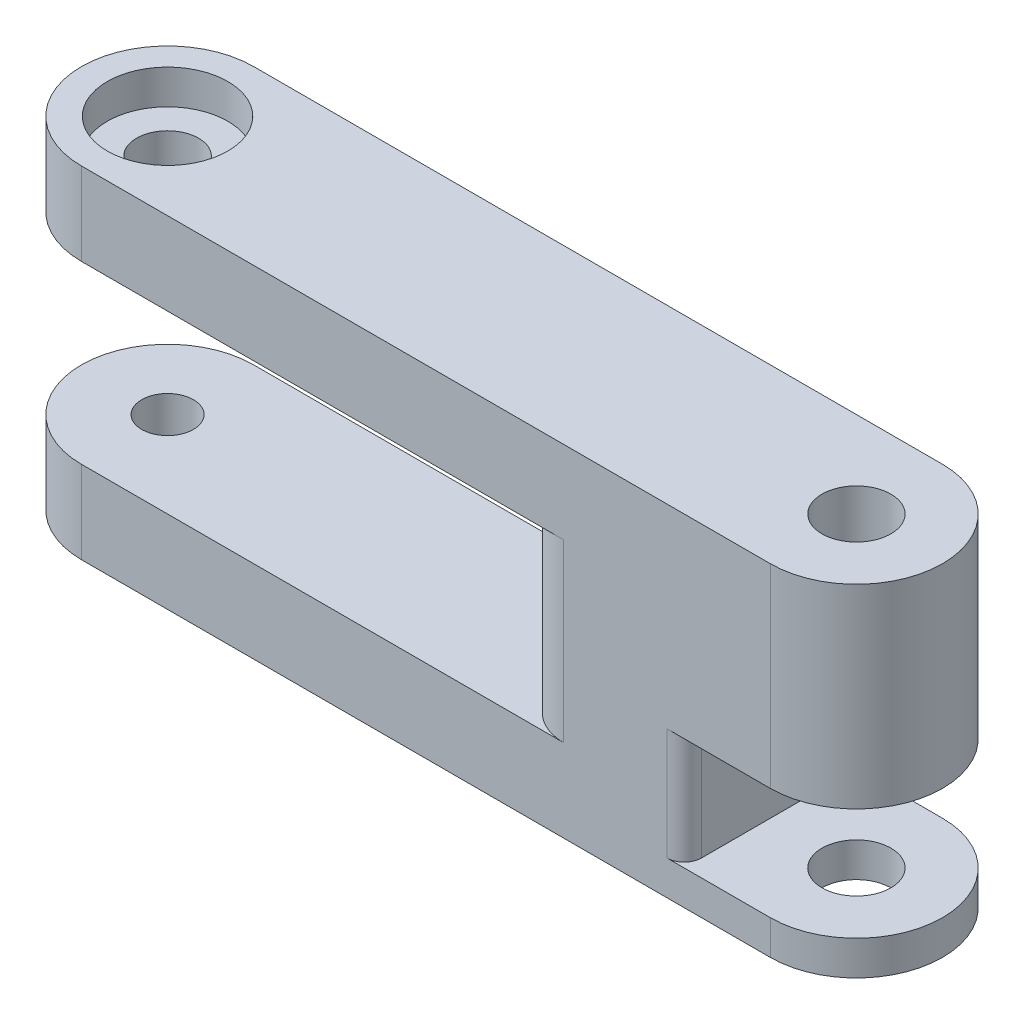
SolidWorks part; units mm, degrees
ref_plane "Front Plane" through (0, 0, 0) normal (0, 0, 1) x (1, 0, 0)
ref_plane "Top Plane" through (0, 0, 0) normal (0, 1, 0) x (1, 0, 0)
ref_plane "Right Plane" through (0, 0, 0) normal (1, 0, 0) x (0, 0, -1)
sketch "Sketch1" plane through (0, 0, 0) normal (0, 1, 0) x (1, 0, 0)
  line L0 (-25.4, 0) -> (25.4, 0) construction
  line L1 (-25.4, 6.35) -> (25.4, 6.35)
  line L2 (-25.4, -6.35) -> (25.4, -6.35)
  arc A0 (-25.4, 6.35) -> (-25.4, -6.35) centre (-25.4, 0) ccw
  arc A1 (25.4, -6.35) -> (25.4, 6.35) centre (25.4, 0) ccw
  circle A2 centre (-25.4, 0) radius 2.286
  circle A3 centre (25.4, 0) radius 2.54
  point P2 (0, 0)
  dimension "D3" = 4.572
  dimension "D4" = 5.08
  dimension "D1" = 50.8
  dimension "D2" = 12.7
extrude "Boss-Extrude1" add sketch "Sketch1" along normal mid plane 25.146
sketch "Sketch2" plane through (0, 0, 6.35) normal (0, 0, 1) x (1, 0, 0)
  line L1 (-31.75, 6.477) -> (6.35, 6.477)
  line L2 (-31.75, 6.477) -> (-31.75, -6.477)
  line L3 (-31.75, -6.477) -> (6.35, -6.477)
  line L4 (6.35, 6.477) -> (6.35, -6.477)
  line L5 (-31.75, 12.573) -> (-31.75, -12.573) construction
  line L6 (0, -12.573) -> (0, 12.573) construction
  line L7 (-25.4, 12.573) -> (25.4, 12.573) construction
  line L8 (-31.75, 0) -> (0, 0) construction
  dimension "D2" = 12.954
  dimension "D3" = 38.1
extrude "Cut-Extrude1" cut sketch "Sketch2" against normal through all
sketch "Sketch3" plane through (0, 12.573, 0) normal (0, 1, 0) x (1, 0, 0)
  circle A0 centre (-25.4, 0) radius 4.445
  dimension "D1" = 8.89
extrude "Cut-Extrude2" cut sketch "Sketch3" against normal blind 2.54
sketch "Sketch4" plane through (0, -6.477, 0) normal (0, 1, 0) x (1, 0, 0)
  circle A0 centre (-25.4, 0) radius 1.905
  circle A1 centre (-25.4, 0) radius 2.286
  dimension "D1" = 3.81
extrude "Boss-Extrude2" add sketch "Sketch4" against normal up to surface (6.096 mm away) up to face at (0, -12.573, 0)
fillet "Fillet1" radius 3.81 2 edges at (6.35, 0, -6.35) (6.35, 0, 6.35)
sketch "Sketch5" plane through (0, 0, 6.35) normal (0, 0, 1) x (1, 0, 0)
  line L0 (31.75, -12.573) -> (31.75, 12.573) construction
  line L1 (19.05, 10.033) -> (31.75, 10.033)
  line L2 (19.05, 10.033) -> (19.05, 1.778)
  line L3 (19.05, 1.778) -> (31.75, 1.778)
  line L4 (31.75, 10.033) -> (31.75, 1.778)
  line L5 (31.75, 12.573) -> (25.4, 12.573) construction
  dimension "D1" = 8.255
  dimension "D2" = 2.54
  dimension "D3" = 12.7
extrude "Cut-Extrude3" [suppressed] cut sketch "Sketch5" against normal through all
sketch "Sketch6" plane through (0, 0, 6.35) normal (0, 0, 1) x (1, 0, 0)
  line L0 (31.75, -12.573) -> (31.75, 12.573) construction
  line L1 (31.75, -1.778) -> (19.05, -1.778)
  line L2 (31.75, -1.778) -> (31.75, -10.033)
  line L3 (31.75, -10.033) -> (19.05, -10.033)
  line L4 (19.05, -1.778) -> (19.05, -10.033)
  line L5 (-25.4, -12.573) -> (25.4, -12.573) construction
  dimension "D1" = 12.7
  dimension "D2" = 2.54
  dimension "D3" = 8.255
extrude "Cut-Extrude4" cut sketch "Sketch6" against normal through all
fillet "Fillet2" radius 1.27 2 edges at (19.05, -5.9055, -6.35) (19.05, -5.9055, 6.35)
fillet "Fillet3" [suppressed] radius 1.27
